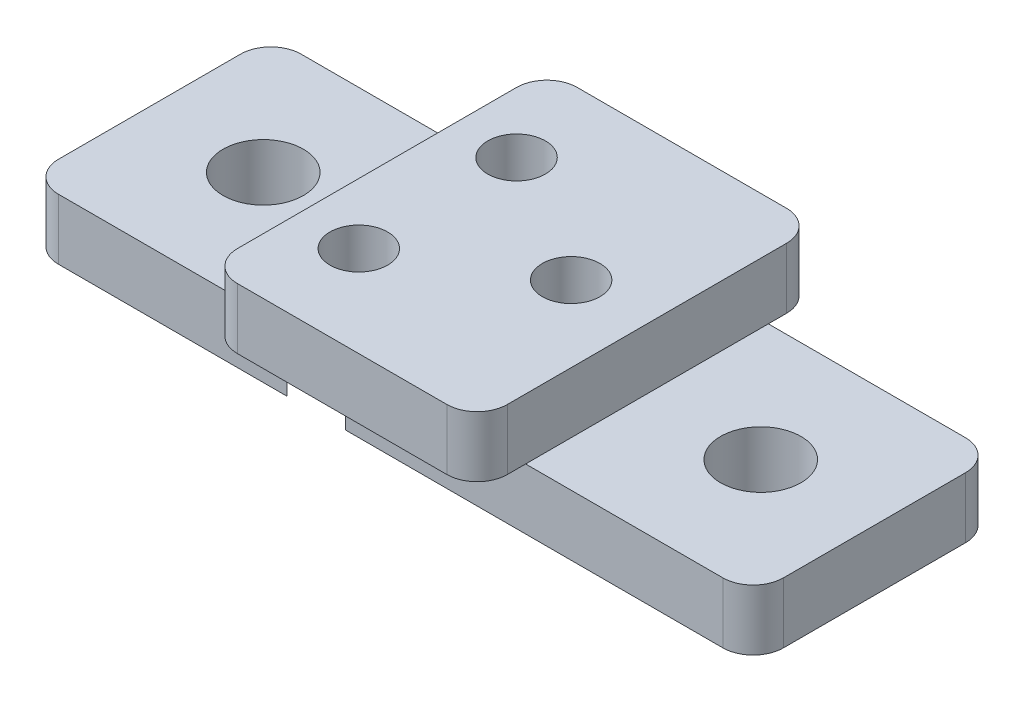
SolidWorks part; units mm, degrees
ref_plane "Front Plane" through (0, 0, 0) normal (0, 0, 1) x (1, 0, 0)
ref_plane "Top Plane" through (0, 0, 0) normal (0, 1, 0) x (1, 0, 0)
ref_plane "Right Plane" through (0, 0, 0) normal (1, 0, 0) x (0, 0, -1)
sketch "Sketch1" plane through (0, 0, 0) normal (0, 1, 0) x (1, 0, 0)
  line L1 (0, 0) -> (47.8, 0)
  line L2 (0, 0) -> (0, 16)
  line L3 (0, 16) -> (47.8, 16)
  line L4 (47.8, 0) -> (47.8, 16)
  dimension "D1" = 16
  dimension "D2" = 47.8
extrude "Boss-Extrude1" add sketch "Sketch1" along normal blind 4
sketch "Sketch2" plane through (0, 4, 0) normal (0, 1, 0) x (1, 0, 0)
  line L0 (15, 8) -> (32.8, 8) construction
  line L1 (15, 19.2) -> (32.8, 19.2)
  line L2 (15, 19.2) -> (15, -3.2)
  line L3 (15, -3.2) -> (32.8, -3.2)
  line L4 (32.8, 19.2) -> (32.8, -3.2)
  line L5 (0, 8) -> (47.8, 8) construction
  line L6 (0, 16) -> (0, 0) construction
  line L7 (47.8, 0) -> (47.8, 16) construction
  circle A0 centre (19, 13.2) radius 1.9
  circle A1 centre (27.8, 8) radius 1.9
  circle A2 centre (19, 2.8) radius 1.9
  dimension "D1" = 3.8
  dimension "D2" = 22.4
  dimension "D3" = 17.8
  dimension "D4" = 4
  dimension "D5" = 6
  dimension "D6" = 5
  dimension "D7" = 15
extrude "Boss-Extrude2" add sketch "Sketch2" along normal blind 4
sketch "Sketch3" plane through (0, 0, 0) normal (0, -1, 0) x (1, 0, 0)
  circle A0 centre (27.8, -8) radius 1.9 construction
  circle A1 centre (19, -13.2) radius 1.9 construction
  circle A2 centre (19, -2.8) radius 1.9 construction
  circle A3 centre (27.8, -8) radius 1.9 construction
  circle A4 centre (19, -13.2) radius 1.9 construction
  circle A5 centre (19, -2.8) radius 1.9 construction
  circle A6 centre (19, -2.8) radius 3.4
  circle A7 centre (27.8, -8) radius 3.4
  circle A8 centre (19, -13.2) radius 3.4
  dimension "D1" = 1.5
  dimension "D2" = 1.5
extrude "Cut-Extrude1" cut sketch "Sketch3" against normal blind 4
sketch "Sketch4" plane through (0, 4, 0) normal (0, 1, 0) x (1, 0, 0)
  line L0 (0, 8) -> (47.8, 8) construction
  line L1 (0, 16) -> (0, 0) construction
  line L2 (47.8, 0) -> (47.8, 16) construction
  line L3 (7.5, 16) -> (7.5, 0) construction
  line L4 (15, 16) -> (0, 16) construction
  line L5 (0, 0) -> (15, 0) construction
  line L6 (40.3, 16) -> (40.3, 0) construction
  line L7 (47.8, 16) -> (32.8, 16) construction
  line L8 (32.8, 0) -> (47.8, 0) construction
  circle A0 centre (7.5, 8) radius 2.65
  circle A1 centre (40.3, 8) radius 2.65
  dimension "D1" = 5.3
extrude "Cut-Extrude2" cut sketch "Sketch4" against normal blind 4
fillet "Fillet1" radius 2 8 edges at (47.8, 2, -16) (47.8, 2, 0) (0, 2, 0) (0, 2, -16) (15, 6, -19.2) (32.8, 6, -19.2) (32.8, 6, 3.2) (15, 6, 3.2)
